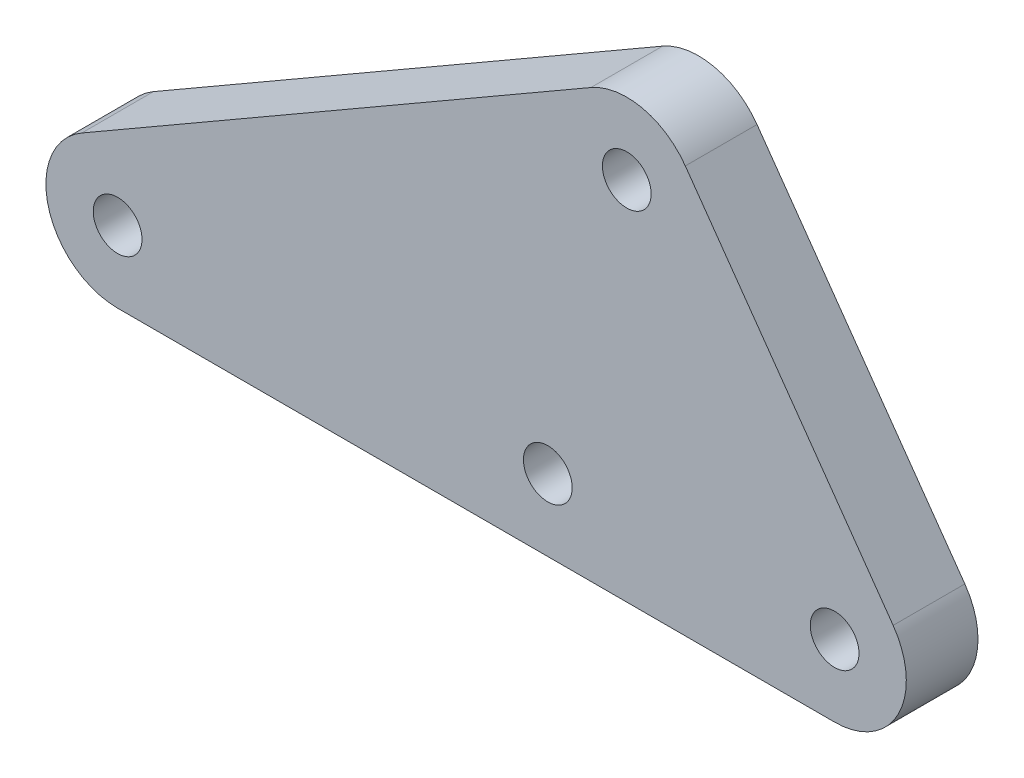
SolidWorks part; units mm, degrees
ref_plane "正面" through (0, 0, 0) normal (0, 0, 1) x (1, 0, 0)
ref_plane "平面" through (0, 0, 0) normal (0, 1, 0) x (1, 0, 0)
ref_plane "右側面" through (0, 0, 0) normal (1, 0, 0) x (0, 0, -1)
sketch "ｽｹｯﾁ1" plane through (0, 0, 0) normal (0, 0, 1) x (1, 0, 0)
  line L0 (0, 0) -> (35, 0)
  line L1 (0, 0) -> (35.507, 20.5)
  line L2 (-18.6603, -5) -> (40.507, 29.1603)
  line L3 (-18.6603, -5) -> (40.507, -5)
  line L5 (40.507, -5) -> (55, -5)
  line L6 (55, -5) -> (55, 37.5278)
  line L7 (40.507, 29.1603) -> (55, 37.5278)
  line L8 (35.507, 20.5) -> (50, 0)
  line L9 (39.5898, 23.3864) -> (55, 1.5889)
  line L10 (35.507, 20.5) -> (39.5898, 23.3864)
  circle A0 centre (35.507, 20.5) radius 1.7
  circle A1 centre (0, 0) radius 1.7
  circle A2 centre (30, 0) radius 1.7
  circle A3 centre (35.507, 20.5) radius 5
  circle A4 centre (30, 0) radius 5
  circle A5 centre (0, 0) radius 5
  circle A6 centre (50, 0) radius 1.7
  circle A7 centre (50, 28.8675) radius 5
  circle A8 centre (50, 0) radius 5
  point P23 (35.507, 0)
  dimension "D3" = 5
  dimension "D5" = 30
  dimension "D6" = 20
  dimension "D7" = 5
  dimension "D8" = 5
  dimension "D9" = 5
  dimension "D1" = 30
  dimension "D2" = 41
  dimension "D4" = 5
extrude "ﾎﾞｽ - 押し出し1" add sketch "ｽｹｯﾁ1" along normal blind 5
